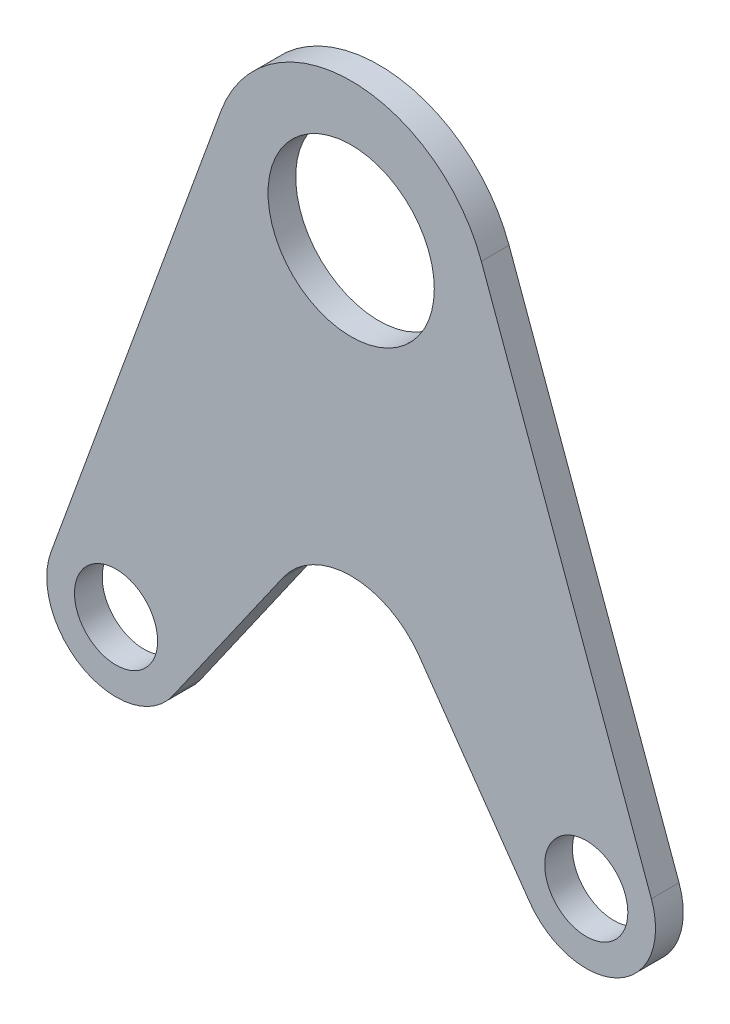
SolidWorks part; units mm, degrees
ref_plane "Front Plane" through (0, 0, 0) normal (0, 0, 1) x (1, 0, 0)
ref_plane "Top Plane" through (0, 0, 0) normal (0, 1, 0) x (1, 0, 0)
ref_plane "Right Plane" through (0, 0, 0) normal (1, 0, 0) x (0, 0, -1)
sketch "Sketch1" plane through (0, 0, 0) normal (0, 0, 1) x (1, 0, 0)
  line L0 (-46.9846, 17.101) -> (-108.332, -151.4495)
  line L1 (46.9846, 17.101) -> (108.332, -151.4495)
  line L2 (-64.3609, -174.3394) -> (-24.5746, -117.5187)
  line L3 (24.5746, -117.5187) -> (64.3609, -174.3394)
  line L4 (0, 0) -> (0, -197.9536) construction
  circle A0 centre (0, 0) radius 30
  arc A1 (46.9846, 17.101) -> (-46.9846, 17.101) centre (0, 0) ccw
  circle A2 centre (-84.8397, -160) radius 15
  arc A3 (-108.332, -151.4495) -> (-64.3609, -174.3394) centre (-84.8397, -160) ccw
  circle A4 centre (84.8397, -160) radius 15
  arc A5 (64.3609, -174.3394) -> (108.332, -151.4495) centre (84.8397, -160) ccw
  arc A6 (-24.5746, -117.5187) -> (24.5746, -117.5187) centre (0, -134.726) cw
  dimension "D1" = 60
  dimension "D2" = 100
  dimension "D3" = 30
  dimension "D4" = 50
  dimension "D9" = 30
  dimension "D5" = 35
  dimension "D6" = 35
  dimension "D7" = 20
  dimension "D8" = 160
extrude "Boss-Extrude1" add sketch "Sketch1" along normal blind 10
